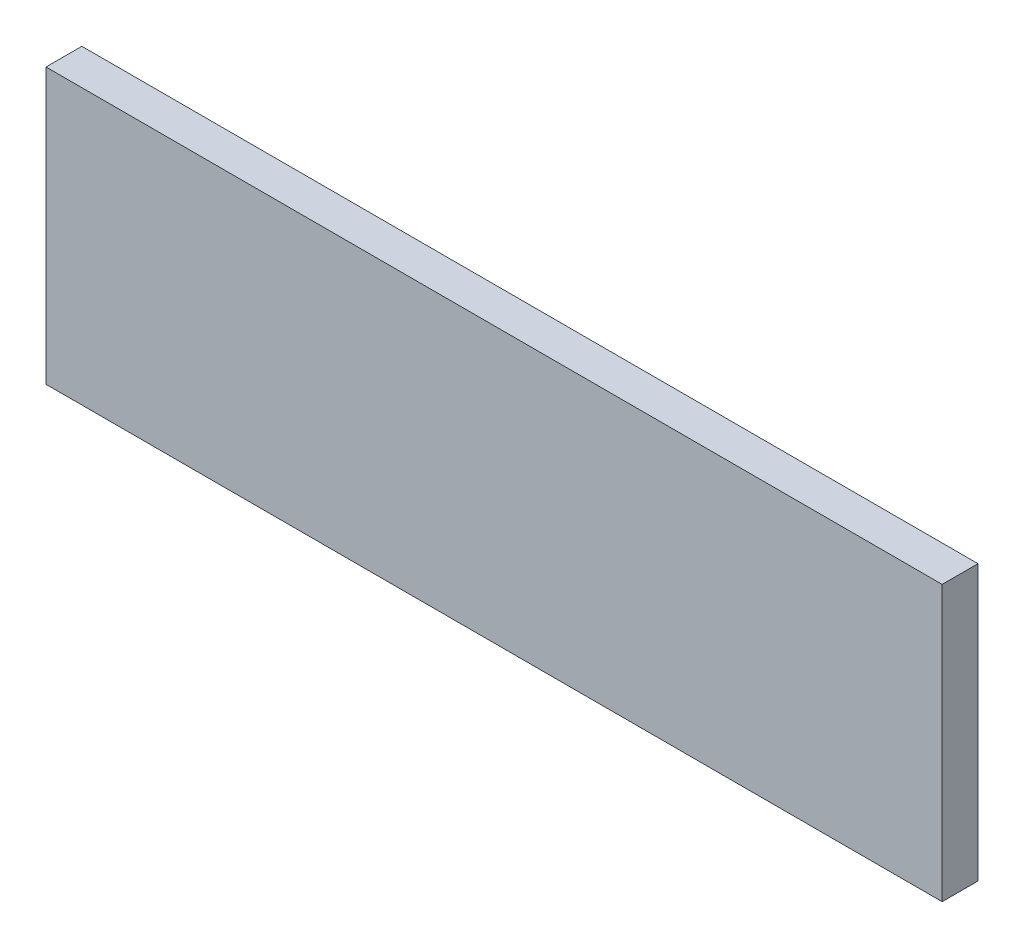
SolidWorks part; units mm, degrees
material "Pine"
ref_plane "Front Plane" through (0, 0, 0) normal (0, 0, 1) x (1, 0, 0)
ref_plane "Top Plane" through (0, 0, 0) normal (0, 1, 0) x (1, 0, 0)
ref_plane "Right Plane" through (0, 0, 0) normal (1, 0, 0) x (0, 0, -1)
sketch "Sketch1" plane through (0, 0, 0) normal (0, 0, 1) x (1, 0, 0)
  line L1 (-75, 23) -> (75, 23)
  line L2 (-75, 23) -> (-75, -23)
  line L3 (-75, -23) -> (75, -23)
  line L4 (75, 23) -> (75, -23)
  line L5 (-75, 23) -> (75, -23) construction
  line L6 (-75, -23) -> (75, 23) construction
  point P0 (0, 0)
  dimension "D1" = 150
  dimension "D2" = 46
extrude "Boss-Extrude1" add sketch "Sketch1" along normal blind 6
